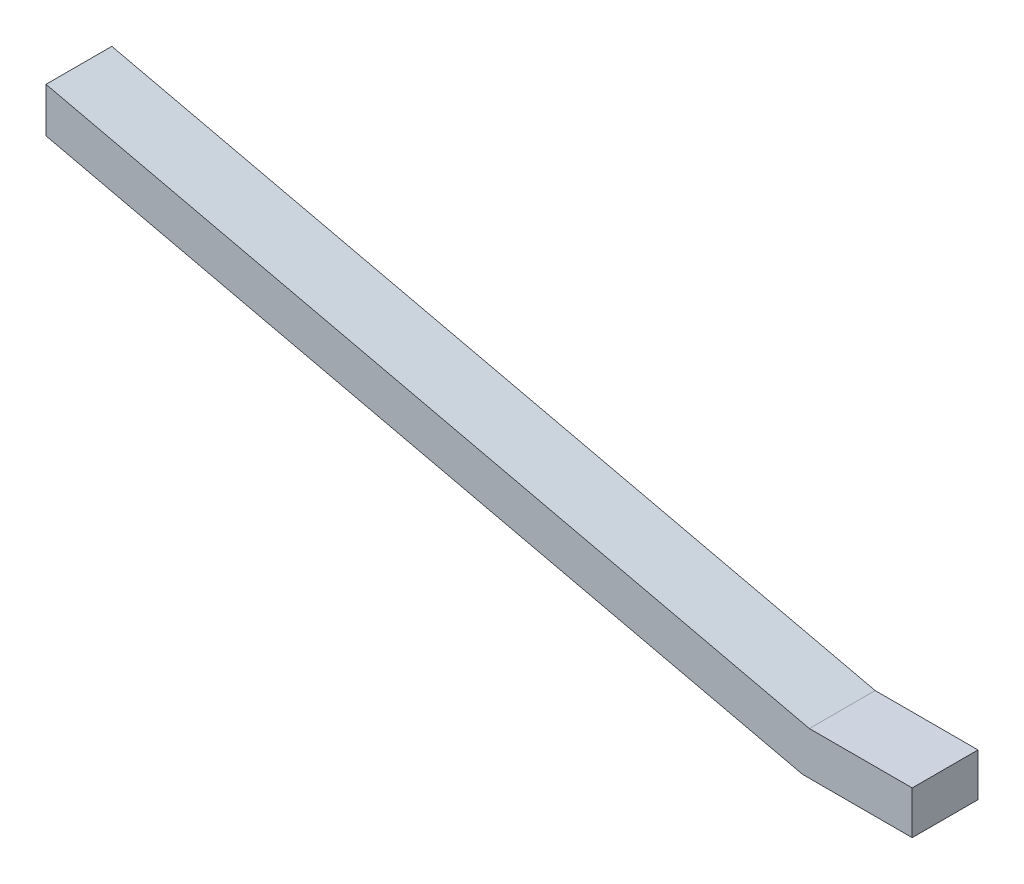
SolidWorks part; units mm, degrees
ref_plane "Alzado" through (0, 0, 0) normal (0, 0, 1) x (1, 0, 0)
ref_plane "Planta" through (0, 0, 0) normal (0, 1, 0) x (1, 0, 0)
ref_plane "Vista lateral" through (0, 0, 0) normal (1, 0, 0) x (0, 0, -1)
sketch "Croquis1" plane through (0, 0, 0) normal (0, 0, 1) x (1, 0, 0)
  line L0 (0, 0) -> (13920.9967, -3213.9153)
  line L1 (13920.9967, -3213.9153) -> (15795.8661, -3213.9153)
  line L2 (0, -4000) -> (0, 0) construction
  line L3 (0, 0) -> (0, -814.9734)
  line L4 (15795.8661, -3213.9153) -> (15795.8661, -4000)
  line L5 (15795.8661, -4000) -> (13795.8661, -4000)
  line L6 (0, -814.9734) -> (13795.8661, -4000)
  dimension "D1" = 13
  dimension "D2" = 4000
  dimension "D3" = 13795.8661
  dimension "D4" = 2000
extrude "Saliente-Extruir1" add sketch "Croquis1" along normal blind 1200
